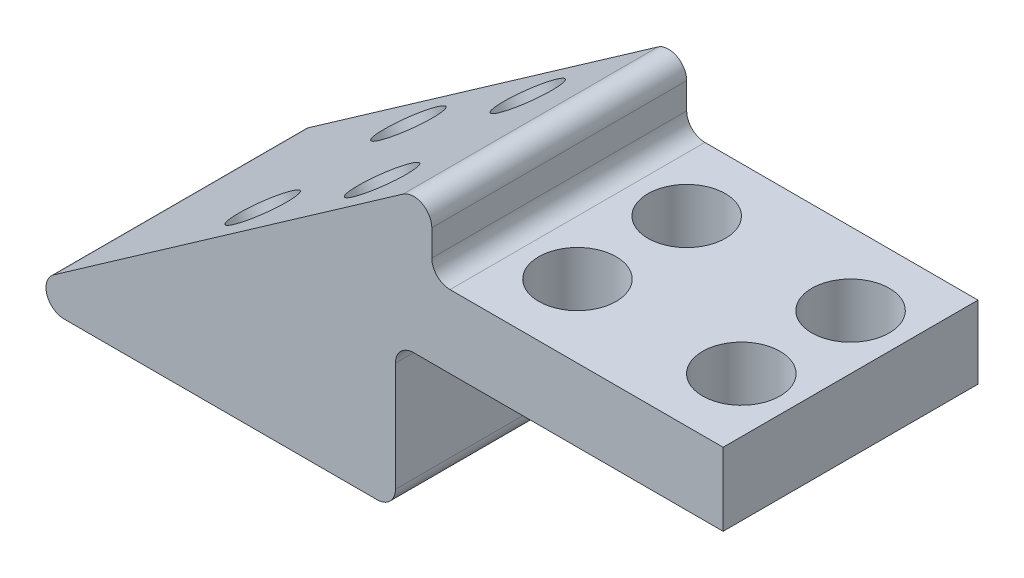
SolidWorks part; units mm, degrees
material "6061 Alloy"
ref_plane "Front Plane" through (0, 0, 0) normal (0, 0, 1) x (1, 0, 0)
ref_plane "Top Plane" through (0, 0, 0) normal (0, 1, 0) x (1, 0, 0)
ref_plane "Right Plane" through (0, 0, 0) normal (1, 0, 0) x (0, 0, -1)
sketch "Sketch1" plane through (0, 0, 0) normal (0, 0, 1) x (1, 0, 0)
  line L0 (0, 0) -> (25.4, 0) construction
  line L1 (0, 0) -> (0, 17.145) construction
  line L2 (0, 0) -> (25.4, 0)
  line L3 (25.4, 0) -> (25.4, 6.35)
  line L4 (0, 0) -> (0, -12.7) construction
  line L5 (0, -12.7) -> (-42.6231, -12.7) construction
  line L6 (-42.6231, -12.7) -> (0, 17.145) construction
  line L8 (0, 13.269) -> (-37.0876, -12.7) construction
  line L9 (25.4, 6.35) -> (0, 6.35)
  line L10 (0, 6.35) -> (0, 13.269)
  line L11 (0, 13.269) -> (-37.0876, -12.7)
  line L13 (-3.175, 0) -> (-3.175, -12.7) construction
  line L14 (0, 0) -> (-3.175, 0)
  line L15 (-3.175, 0) -> (-3.175, -12.7)
  line L16 (-3.175, -12.7) -> (-37.0876, -12.7)
  dimension "D1" = 25.4
  dimension "D2" = 17.145
  dimension "D3" = 6.35
  dimension "D4" = 12.7
  dimension "D5" = 35
  dimension "D6" = 3.175
  dimension "D7" = 3.175
extrude "Boss-Extrude1" add sketch "Sketch1" along normal mid plane 22.225
sketch "Sketch3" plane through (0, 6.35, 0) normal (0, 1, 0) x (1, 0, 0)
  line L0 (0, 4.7625) -> (25.4, 4.7625) construction
  line L1 (0, 0) -> (25.4, 0) construction
  line L2 (0, -11.1125) -> (0, 11.1125) construction
  line L3 (0, -11.1125) -> (0, 11.1125) construction
  line L4 (25.4, -11.1125) -> (25.4, 11.1125) construction
  line L6 (0, -4.7625) -> (25.4, -4.7625) construction
  point P5 (6.35, 4.7625)
  point P6 (20.6375, 4.7625)
  point P14 (6.35, -4.7625)
  point P15 (20.6375, -4.7625)
  dimension "D1" = 6.35
  dimension "D2" = 20.6375
  dimension "D3" = 9.525
hole_wizard "1/4 Clearance Hole1" positions "Sketch4" profile "Sketch5" hole size "1/4" standard "ANSI Inch" end condition up to next
sketch "Sketch4" plane through (0, 6.35, 0) normal (0, 1, 0) x (1, 0, 0)
  point P0 (6.35, 4.7625)
  point P3 (20.6375, 4.7625)
  point P6 (6.35, -4.7625)
  point P9 (20.6375, -4.7625)
sketch "Sketch5" plane through (6.35, 6.35, -4.7625) normal (1, 0, 0) x (0, 0, 1)
  line L0 (0, 0) -> (0, 6.35)
  line L1 (0, 6.35) -> (3.3782, 6.35)
  line L2 (3.3782, 6.35) -> (3.3782, 0)
  line L5 (3.3782, 0) -> (0, 0)
  line L11 (0, -6.35) -> (0, 107.95) construction
  dimension "Thru Hole Dia." = 6.7564
  dimension "Thru Hole Depth" = 6.35
sketch "Sketch7" plane through (-6.2344, 8.9037, 0) normal (-0.5736, 0.8192, 0) x (0.8192, 0.5736, 0)
  line L0 (-37.6648, 0) -> (7.6108, 0) construction
  line L1 (-37.6648, -11.1125) -> (-37.6648, 11.1125) construction
  line L2 (7.6108, -11.1125) -> (7.6108, 11.1125) construction
  line L3 (-16.2017, 6.35) -> (-3.5017, 6.35) construction
  line L4 (-3.5017, 6.35) -> (-3.5017, -6.35) construction
  line L5 (-3.5017, -6.35) -> (-16.2017, -6.35) construction
  line L6 (-16.2017, -6.35) -> (-16.2017, 6.35) construction
  line L7 (7.6108, 11.1125) -> (-37.6648, 11.1125) construction
  line L8 (7.6108, -11.1125) -> (-37.6648, -11.1125) construction
  point P6 (-16.2017, 6.35)
  point P7 (-3.5017, 6.35)
  point P8 (-3.5017, -6.35)
  point P9 (-16.2017, -6.35)
  dimension "D1" = 11.1125
  dimension "D2" = 12.7
  dimension "D3" = 4.7625
  dimension "D4" = 4.7625
fillet "Fillet1" radius 1.5875 5 edges at (-3.175, -12.7, 0) (-37.0876, -12.7, 0) (0, 13.269, 0) (-3.175, 0, 0) (0, 6.35, 0)
hole_wizard "Tap Drill for 1/4-20 Tap1" positions "Sketch8" profile "Sketch9" hole size "1/4-20" standard "ANSI Inch"
sketch "Sketch8" plane through (-6.2344, 8.9037, 0) normal (-0.5736, 0.8192, 0) x (0.8192, 0.5736, 0)
  point P0 (-16.2017, 6.35)
  point P3 (-3.5017, 6.35)
  point P6 (-3.5017, -6.35)
  point P9 (-16.2017, -6.35)
sketch "Sketch9" plane through (-19.5061, -0.3892, -6.35) normal (0, 0, 1) x (-0.8192, -0.5736, 0)
  line L0 (0, 0) -> (0, 11.0588)
  line L1 (0, 11.0588) -> (2.5527, 9.525)
  line L2 (2.5527, 9.525) -> (2.5527, 0)
  line L5 (2.5527, 0) -> (0, 0)
  line L10 (0, 11.0588) -> (-2.5527, 9.525) construction
  line L11 (0, -6.35) -> (0, 107.95) construction
  dimension "Hole Dia." = 5.1054
  dimension "Hole Depth" = 9.525
  dimension "Drill Angle" = 118
